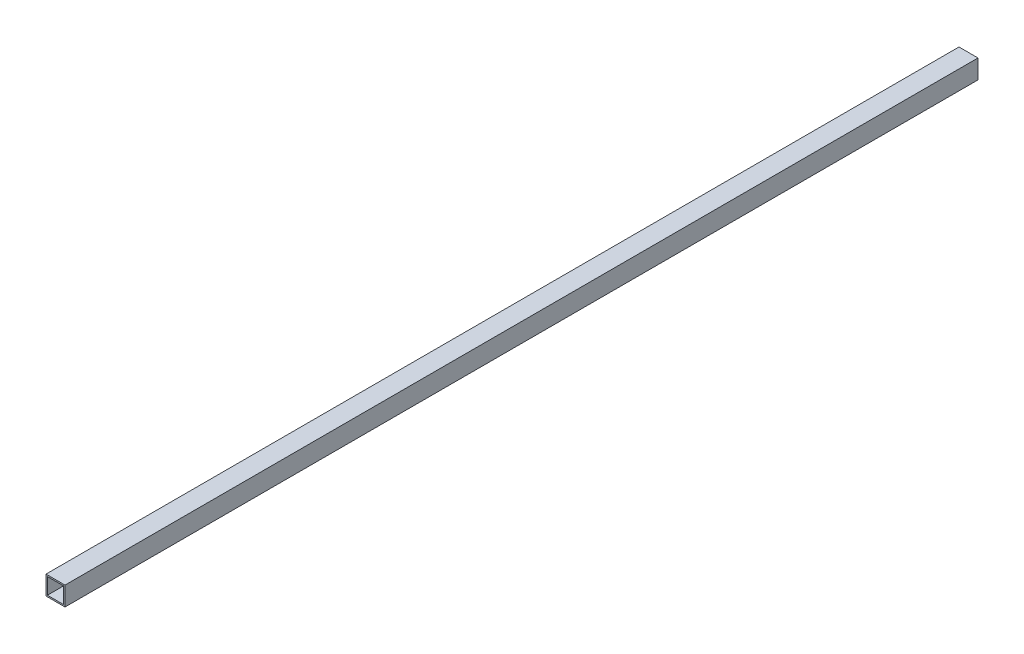
SolidWorks part; units mm, degrees
ref_plane "Front Plane" through (0, 0, 0) normal (0, 0, 1) x (1, 0, 0)
ref_plane "Top Plane" through (0, 0, 0) normal (0, 1, 0) x (1, 0, 0)
ref_plane "Right Plane" through (0, 0, 0) normal (1, 0, 0) x (0, 0, -1)
sketch "Sketch1" plane through (0, 0, 0) normal (0, 0, 1) x (1, 0, 0)
  line L1 (-20, 20) -> (20, 20)
  line L2 (-20, 20) -> (-20, -20)
  line L3 (-20, -20) -> (20, -20)
  line L4 (20, 20) -> (20, -20)
  line L5 (-20, 20) -> (20, -20) construction
  line L6 (-20, -20) -> (20, 20) construction
  point P0 (0, 0)
  dimension "D1" = 40
  dimension "D2" = 40
extrude "Boss-Extrude1" add sketch "Sketch1" along normal blind 1920
sketch "Sketch2" plane through (0, 0, 0) normal (0, 0, -1) x (-1, 0, 0)
  line L1 (-17, 17) -> (17, 17)
  line L2 (-17, 17) -> (-17, -17)
  line L3 (-17, -17) -> (17, -17)
  line L4 (17, 17) -> (17, -17)
  line L5 (-17, 17) -> (17, -17) construction
  line L6 (-17, -17) -> (17, 17) construction
  point P0 (0, 0)
  dimension "D1" = 34
  dimension "D2" = 34
extrude "Cut-Extrude1" cut sketch "Sketch2" against normal blind 1920
